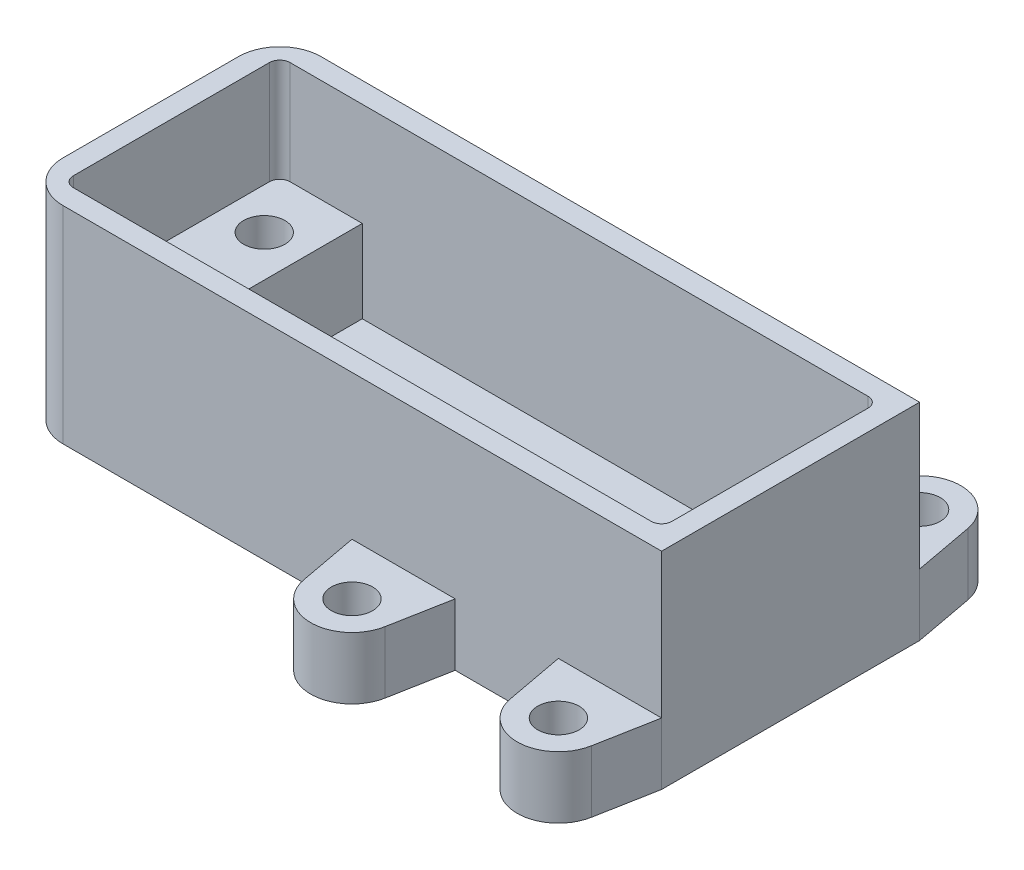
SolidWorks part; units mm, degrees
ref_plane "前视基准面" through (0, 0, 0) normal (0, 0, 1) x (1, 0, 0)
ref_plane "上视基准面" through (0, 0, 0) normal (0, 1, 0) x (1, 0, 0)
ref_plane "右视基准面" through (0, 0, 0) normal (1, 0, 0) x (0, 0, -1)
sketch "草图1" plane through (0, 0, 0) normal (0, 1, 0) x (1, 0, 0)
  line L1 (-31, -12.5) -> (31, -12.5)
  line L2 (-31, -12.5) -> (-31, 12.5)
  line L3 (-31, 12.5) -> (31, 12.5)
  line L4 (31, -12.5) -> (31, 12.5)
  line L5 (-31, -12.5) -> (31, 12.5) construction
  line L6 (-31, 12.5) -> (31, -12.5) construction
  point P0 (0, 0)
  dimension "D1" = 62
  dimension "D2" = 25
extrude "凸台-拉伸1" add sketch "草图1" along normal blind 20
shell "抽壳1" thickness 2
sketch "草图2" plane through (0, 2, 0) normal (0, 1, 0) x (1, 0, 0)
  line L0 (-29, -10.5) -> (29, -10.5) construction
  line L1 (-29, 10.5) -> (-21, 10.5)
  line L2 (-29, 10.5) -> (-29, -10.5)
  line L3 (-29, -10.5) -> (-21, -10.5)
  line L4 (-21, 10.5) -> (-21, -10.5)
  line L5 (29, 10.5) -> (-29, 10.5) construction
  line L6 (21, 10.5) -> (29, 10.5)
  line L7 (21, 10.5) -> (21, -10.5)
  line L8 (21, -10.5) -> (29, -10.5)
  line L9 (29, 10.5) -> (29, -10.5)
  dimension "D1" = 8
  dimension "D2" = 8
extrude "凸台-拉伸2" add sketch "草图2" along normal blind 8
sketch "草图3" plane through (0, 10, 0) normal (0, 1, 0) x (1, 0, 0)
  line L2 (29, -10.5) -> (29, 10.5) construction
  line L3 (29, 10.5) -> (21, 10.5) construction
  line L4 (0, 0) -> (0, 14.9506) construction
  circle A0 centre (25, 5) radius 2
  circle A1 centre (25, -5) radius 2
  circle A2 centre (-25, -5) radius 2
  circle A3 centre (-25, 5) radius 2
  circle A4 centre (-25, -5) radius 2
  circle A5 centre (-25, 5) radius 2
  dimension "D1" = 4
  dimension "D2" = 4
  dimension "D3" = 5.5
  dimension "D4" = 10
extrude "切除-拉伸1" cut sketch "草图3" against normal through all contours A3 | A2 | A0 | A1
sketch "草图4" plane through (0, 2, 0) normal (0, 1, 0) x (1, 0, 0)
  line L0 (-21, -10.5) -> (-21, 10.5) construction
  circle A0 centre (-12, 0) radius 6
  dimension "D1" = 9
  dimension "D2" = 12
extrude "切除-拉伸2" cut sketch "草图4" against normal through all
sketch "草图5" plane through (0, 0, 0) normal (0, 1, 0) x (1, 0, 0)
  line L0 (22.0676, 18.2324) -> (21, 12.5)
  line L1 (31, 12.5) -> (-31, 12.5) construction
  line L2 (21, 12.5) -> (31, 12.5)
  line L3 (31, 12.5) -> (29.9324, 18.2324)
  line L4 (26, 17.5) -> (26, 12.5) construction
  line L5 (2.0676, 18.2324) -> (1, 12.5)
  line L6 (11, 12.5) -> (9.9324, 18.2324)
  line L7 (1, 12.5) -> (11, 12.5)
  arc A0 (29.9324, 18.2324) -> (22.0676, 18.2324) centre (26, 17.5) ccw
  circle A1 centre (26, 17.5) radius 2
  arc A2 (9.9324, 18.2324) -> (2.0676, 18.2324) centre (6, 17.5) ccw
  circle A3 centre (6, 17.5) radius 2
  dimension "D3" = 4
  dimension "D4" = 4
  dimension "D6" = 20
  dimension "D1" = 5
  dimension "D2" = 5
  dimension "D5" = 2
extrude "凸台-拉伸3" add sketch "草图5" along normal blind 6
mirror "镜向1" about plane through (0, 0, 0) normal (0, 0, 1) of "凸台-拉伸3"
fillet "圆角1" radius 4 2 edges at (-31, 10, -12.5) (-31, 10, 12.5)
fillet "圆角2" radius 1 4 edges at (29, 15, -10.5) (-29, 15, 10.5) (29, 15, 10.5) (-29, 15, -10.5)
move or copy body "实体-移动/复制1" [suppressed] bodies to move or copy 111
move or copy body "实体-移动/复制2" [suppressed] bodies to move or copy 112 parameters "D1"=0, "D2"=0, "D3"=0
move or copy body "实体-移动/复制3" [suppressed] bodies to move or copy 113 parameters "D1"=0, "D2"=0, "D3"=0
